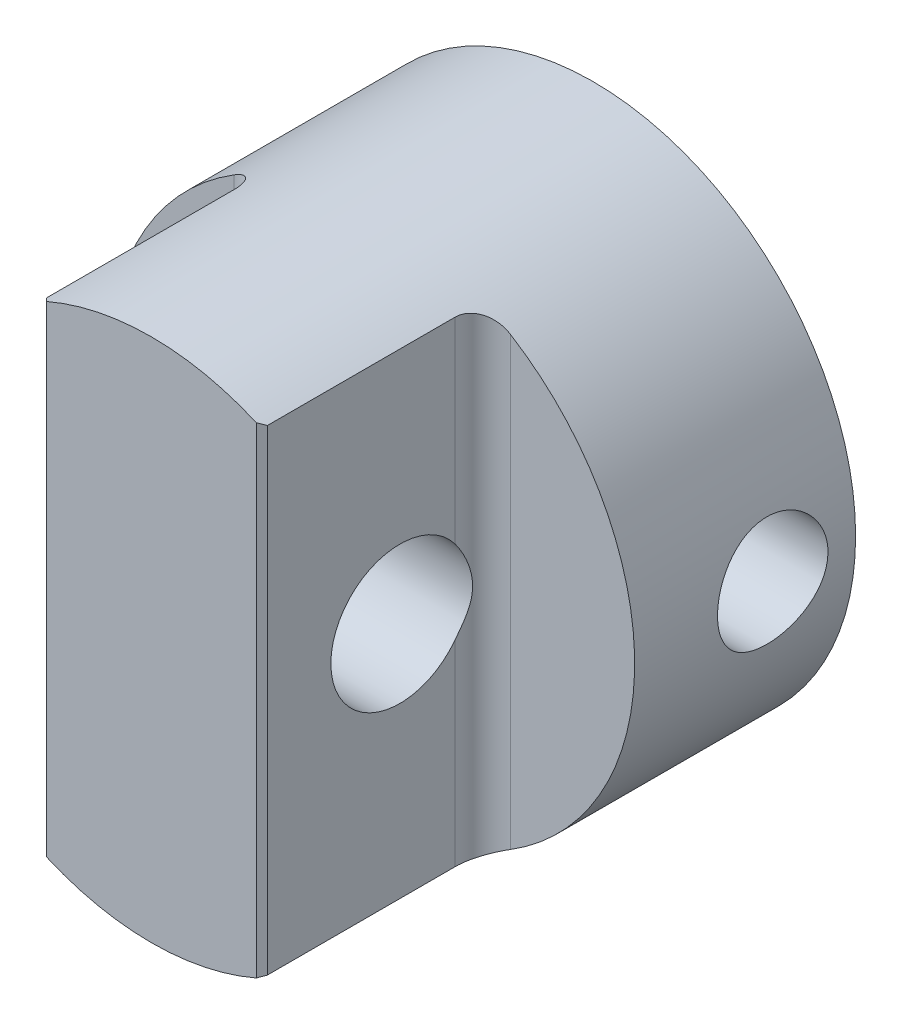
SolidWorks part; units mm, degrees
ref_plane "Спереди" through (0, 0, 0) normal (0, 0, 1) x (1, 0, 0)
ref_plane "Сверху" through (0, 0, 0) normal (0, 1, 0) x (1, 0, 0)
ref_plane "Справа" through (0, 0, 0) normal (1, 0, 0) x (0, 0, -1)
sketch "Эскиз1" plane through (0, 0, 0) normal (0, 0, 1) x (1, 0, 0)
  circle A0 centre (0, 0) radius 47.5
  dimension "D1" = 95
extrude "Бобышка-Вытянуть1" add sketch "Эскиз1" along normal blind 80
sketch "Эскиз2" plane through (0, 0, 80) normal (0, 0, 1) x (1, 0, 0)
  line L0 (0, 47.5) -> (0, -65.2008) construction
  line L1 (20, -43.0842) -> (20, 43.0842)
  line L2 (-20, -43.0842) -> (-20, 43.0842)
  arc A0 (-20, 43.0842) -> (-20, -43.0842) centre (0, 0) ccw
  circle A1 centre (0, 0) radius 47.5 construction
  arc A2 (20, -43.0842) -> (20, 43.0842) centre (0, 0) ccw
  dimension "D1" = 40
extrude "Вырез-Вытянуть1" cut sketch "Эскиз2" against normal blind 40
fillet "Скругление1" radius 5 2 edges at (-20, 0, 40) (20, 0, 40)
sketch "Эскиз3" plane through (-20, 0, 0) normal (-1, 0, 0) x (0, 0, 1)
  line L0 (45, 0) -> (80, 0) construction
  line L1 (45, 43.0842) -> (45, -43.0842) construction
  line L2 (80, -43.0842) -> (80, 43.0842) construction
  circle A0 centre (55, 0) radius 12.5
  dimension "D1" = 25
  dimension "D2" = 25
extrude "Вырез-Вытянуть2" cut sketch "Эскиз3" against normal through all
chamfer "Фаска1" distance 1 angle 45 2 edges at (-20, 0, 80) (20, 0, 80)
chamfer "Фаска2" [suppressed] distance 3 angle 45
sketch "Эскиз4" plane through (0, 0, 0) normal (1, 0, 0) x (0, 0, -1)
  line L0 (-82.3564, 0) -> (29.3425, 0) construction
  circle A0 centre (-15, 0) radius 10
  dimension "D1" = 20
  dimension "D2" = 15
extrude "Вырез-Вытянуть3" cut sketch "Эскиз4" against normal through all and the other way through all
